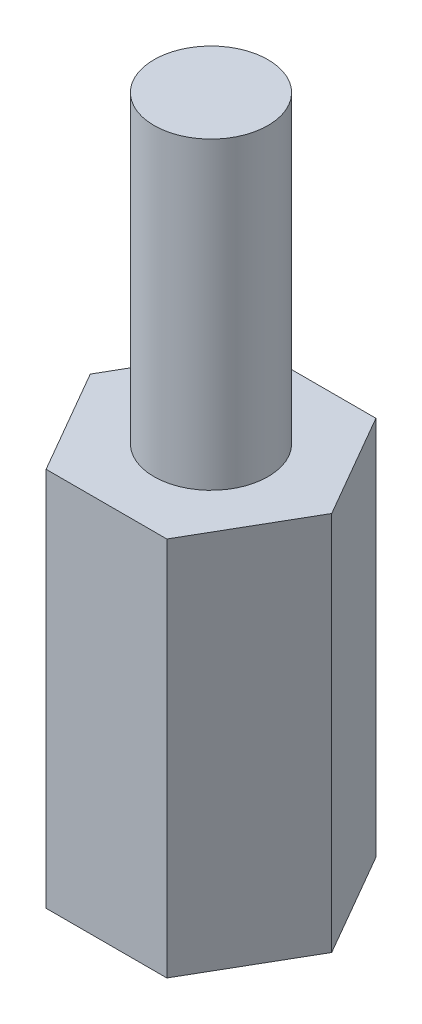
SolidWorks part; units mm, degrees
ref_plane "Front" through (0, 0, 0) normal (0, 0, 1) x (1, 0, 0)
ref_plane "Top" through (0, 0, 0) normal (0, 1, 0) x (1, 0, 0)
ref_plane "Right" through (0, 0, 0) normal (1, 0, 0) x (0, 0, -1)
sketch "Sketch1" plane through (0, 0, 0) normal (0, 1, 0) x (1, 0, 0)
  line L1 (3.1754, 0) -> (1.5877, 2.75)
  line L2 (1.5877, 2.75) -> (-1.5877, 2.75)
  line L3 (-1.5877, 2.75) -> (-3.1754, 0)
  line L4 (-3.1754, 0) -> (-1.5877, -2.75)
  line L5 (-1.5877, -2.75) -> (1.5877, -2.75)
  line L6 (1.5877, -2.75) -> (3.1754, 0)
  circle A0 centre (0, 0) radius 2.75 construction
  dimension "D1" = 5.5
extrude "Boss-Extrude1" add sketch "Sketch1" against normal blind 10
sketch "Sketch2" plane through (0, 0, 0) normal (0, 1, 0) x (1, 0, 0)
  circle A0 centre (0, 0) radius 1.5
  dimension "D1" = 3
extrude "Boss-Extrude2" add sketch "Sketch2" along normal blind 8
